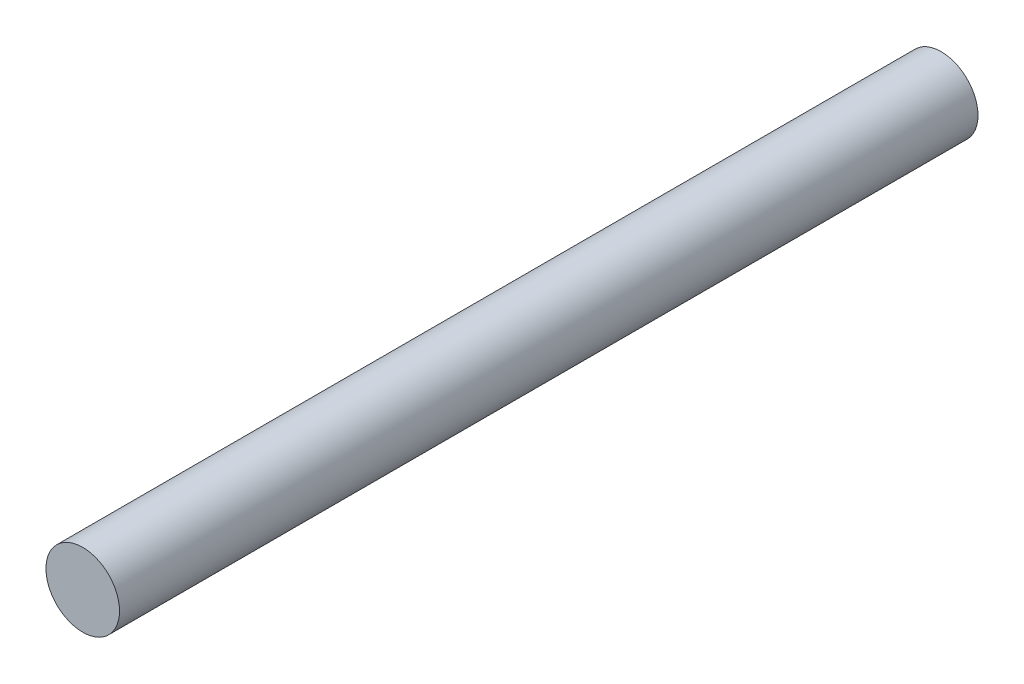
SolidWorks part; units mm, degrees
ref_plane "Front Plane" through (0, 0, 0) normal (0, 0, 1) x (1, 0, 0)
ref_plane "Top Plane" through (0, 0, 0) normal (0, 1, 0) x (1, 0, 0)
ref_plane "Right Plane" through (0, 0, 0) normal (1, 0, 0) x (0, 0, -1)
sketch "Sketch1" plane through (0, 0, 0) normal (0, 0, 1) x (1, 0, 0)
  circle A0 centre (0, 0) radius 30
  dimension "D1" = 60
extrude "Boss-Extrude1" add sketch "Sketch1" along normal blind 700
